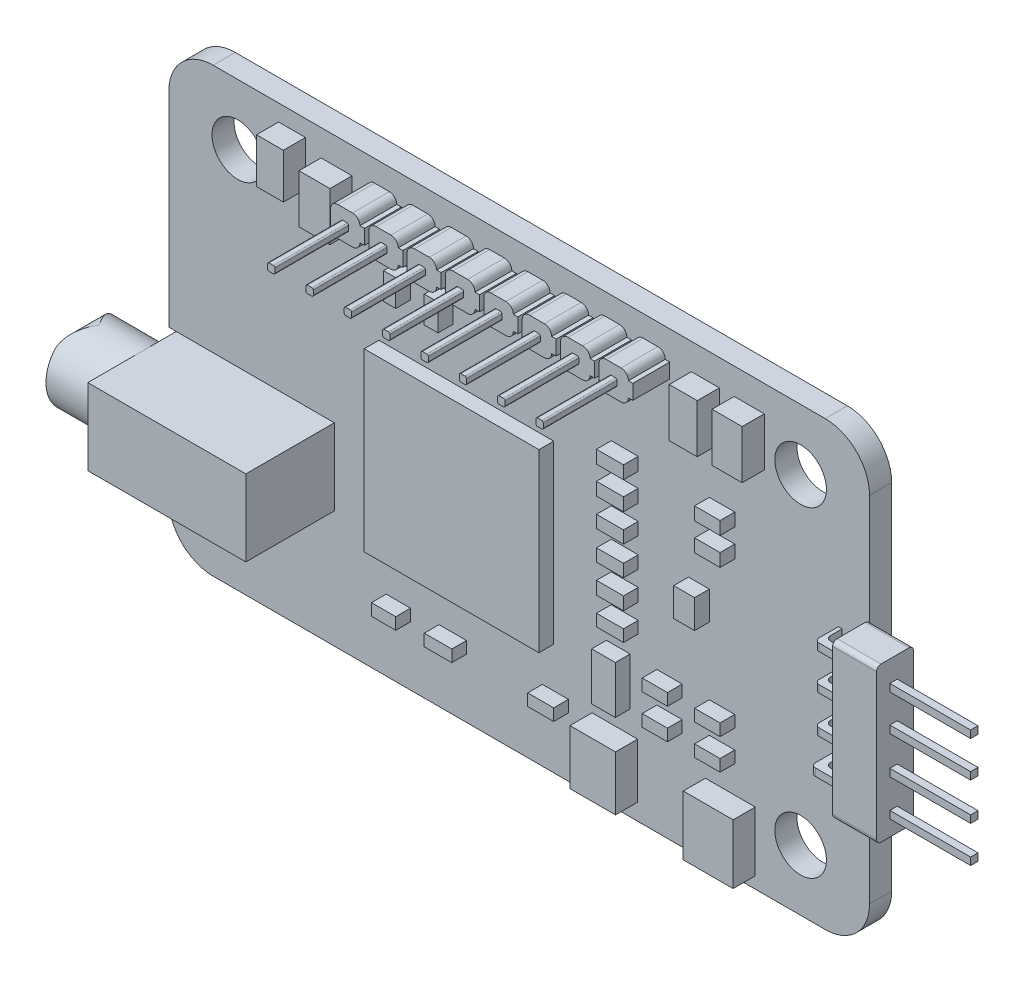
SolidWorks part; units mm, degrees
ref_plane "Alzado" through (0, 0, 0) normal (0, 0, 1) x (1, 0, 0)
ref_plane "Planta" through (0, 0, 0) normal (0, 1, 0) x (1, 0, 0)
ref_plane "Vista lateral" through (0, 0, 0) normal (1, 0, 0) x (0, 0, -1)
sketch "Croquis1" plane through (0, 0, 0) normal (0, 0, 1) x (1, 0, 0)
  line L1 (-20.75, -15) -> (20.75, -15)
  line L2 (-23.75, -12) -> (-23.75, 12)
  line L3 (-20.75, 15) -> (20.75, 15)
  line L4 (23.75, -12) -> (23.75, 12)
  line L5 (-23.75, -15) -> (23.75, 15) construction
  line L6 (-23.75, 15) -> (23.75, -15) construction
  arc A0 (-20.75, -15) -> (-23.75, -12) centre (-20.75, -12) cw
  arc A1 (20.75, -15) -> (23.75, -12) centre (20.75, -12) ccw
  arc A2 (20.75, 15) -> (23.75, 12) centre (20.75, 12) cw
  arc A3 (-23.75, 12) -> (-20.75, 15) centre (-20.75, 12) cw
  point P0 (0, 0)
  dimension "D3" = 3
  dimension "D1" = 47.5
  dimension "D2" = 30
extrude "Saliente-Extruir1" add sketch "Croquis1" along normal blind 1.5 contours L3 A2 L4 A1 L1 A0 L2 A3
sketch "Dibujo_1" plane through (0, 0, 1.5) normal (0, 0, 1) x (1, 0, 0)
  line L0 (72.1693, 147.6706) -> (477.5026, 147.6706) construction
sketch "Croquis3" plane through (0, 0, 1.5) normal (0, 0, 1) x (1, 0, 0)
  circle A0 centre (-19.0796, -10.8807) radius 1.75
  dimension "D1" = 3.5
extrude "Cortar-Extruir1" cut sketch "Croquis3" against normal blind 3
ref_plane "Plano1" through (0, 0, 0) normal (0, -1, 0) x (-1, 0, 0)
ref_plane "Plano2" through (0, 0, 0) normal (-1, 0, 0) x (0, 0, 1)
mirror "Simetría1" about plane through (0, 0, 0) normal (0, -1, 0) of "Cortar-Extruir1"
mirror "Simetría2" about plane through (0, 0, 0) normal (-1, 0, 0) of "Simetría1", "Cortar-Extruir1"
sketch "Croquis4" plane through (0, 0, 1.5) normal (0, 0, 1) x (1, 0, 0)
  line L1 (-9.5072, 4.472) -> (2.338, 4.472)
  line L2 (-9.5072, 4.472) -> (-9.5072, -7.4522)
  line L3 (-9.5072, -7.4522) -> (2.338, -7.4522)
  line L4 (2.338, 4.472) -> (2.338, -7.4522)
extrude "Saliente-Extruir2" add sketch "Croquis4" along normal blind 1
sketch "Croquis5" plane through (0, 0, 1.5) normal (0, 0, 1) x (1, 0, 0)
  line L0 (-8.2982, 13.0504) -> (-7.9934, 13.0504)
  line L1 (-9.7982, 13.5504) -> (-8.7982, 13.5504)
  line L2 (-10.2982, 13.0504) -> (-10.2982, 12.0504)
  line L3 (-9.7982, 11.5504) -> (-8.7982, 11.5504)
  line L4 (-8.2982, 13.0504) -> (-8.2982, 12.0504) construction
  line L5 (-7.9934, 13.0504) -> (-7.9934, 12.0504)
  line L6 (-8.2982, 12.0504) -> (-7.9934, 12.0504)
  arc A0 (-10.2982, 12.0504) -> (-9.7982, 11.5504) centre (-9.7982, 12.0504) ccw
  arc A1 (-8.7982, 11.5504) -> (-8.2982, 12.0504) centre (-8.7982, 12.0504) ccw
  arc A2 (-8.7982, 13.5504) -> (-8.2982, 13.0504) centre (-8.7982, 13.0504) cw
  arc A3 (-9.7982, 13.5504) -> (-10.2982, 13.0504) centre (-9.7982, 13.0504) ccw
  dimension "D1" = 0.5
  dimension "D2" = 2
  dimension "D3" = 2
extrude "Saliente-Extruir3" add sketch "Croquis5" along normal blind 2.5
sketch "Croquis6" plane through (0, 0, 4) normal (0, 0, 1) x (1, 0, 0)
  line L0 (-10.1518, 11.6968) -> (-8.4447, 13.4039) construction
  line L2 (-9.4618, 12.2868) -> (-9.1618, 12.2868)
  line L3 (-9.5618, 12.3868) -> (-9.5618, 12.6868)
  line L4 (-9.4618, 12.7868) -> (-9.1618, 12.7868)
  line L5 (-9.0618, 12.3868) -> (-9.0618, 12.6868)
  line L6 (-9.5618, 12.2868) -> (-9.0618, 12.7868) construction
  arc A2 (-10.2982, 12.0504) -> (-9.7982, 11.5504) centre (-9.7982, 12.0504) ccw construction
  arc A3 (-8.2982, 13.0504) -> (-8.7982, 13.5504) centre (-8.7982, 13.0504) ccw construction
  arc A4 (-9.4618, 12.2868) -> (-9.5618, 12.3868) centre (-9.4618, 12.3868) cw
  arc A5 (-9.1618, 12.2868) -> (-9.0618, 12.3868) centre (-9.1618, 12.3868) ccw
  arc A6 (-9.1618, 12.7868) -> (-9.0618, 12.6868) centre (-9.1618, 12.6868) cw
  arc A7 (-9.5618, 12.6868) -> (-9.4618, 12.7868) centre (-9.4618, 12.6868) cw
  point P8 (-9.2982, 12.5504)
  point P15 (-9.2982, 12.5504)
  point P26 (-9.5618, 12.7868)
  dimension "D3" = 0.1
  dimension "D1" = 0.5
  dimension "D2" = 0.5
extrude "Saliente-Extruir4" add sketch "Croquis6" along normal blind 5
pattern_linear "MatrizL1" count 8 spacing 2.6 along (1, 0, 0) of "Saliente-Extruir3", "Saliente-Extruir4"
sketch "Croquis8" plane through (-23.75, 0, 0) normal (-1, 0, 0) x (0, 0, 1)
  line L0 (1.5, -12) -> (1.5, 12) construction
  line L1 (1.5, -1.8848) -> (0, -1.8848)
  line L2 (1.5, -1.8848) -> (1.5, -7.0554)
  line L3 (1.5, -7.0554) -> (0, -7.0554)
  line L4 (0, -1.8848) -> (0, -7.0554)
  line L5 (0, -12) -> (0, 12) construction
extrude "Saliente-Extruir6" add sketch "Croquis8" along normal blind 3.5
fillet "Redondeo1" radius 1 2 edges at (-27.25, -1.8848, 0.75) (-27.25, -7.0554, 0.75)
ref_plane "Plano4" through (0, 0, 1.5) normal (0, 0, 1) x (1, 0, 0)
sketch "Croquis15" plane through (0, 0, 1.5) normal (0, 0, 1) x (1, 0, 0)
  line L0 (23.75, -12) -> (23.75, 12) construction
  line L1 (23.75, 4.6797) -> (26.7262, 4.6797)
  line L2 (23.75, 4.6797) -> (23.75, 3.24)
  line L3 (23.75, -5.7836) -> (26.7262, -5.7836)
  line L4 (32.2024, 3.24) -> (32.2024, 2.74)
  line L5 (32.2024, 0.7974) -> (32.2024, 0.2974)
  line L6 (32.2024, 2.74) -> (26.7262, 2.74)
  line L7 (23.75, -4.7176) -> (23.75, -5.7836)
  line L8 (32.2024, 0.7974) -> (26.7262, 0.7974)
  line L9 (26.7262, 2.74) -> (26.7262, 0.7974)
  line L10 (32.2024, 0.2974) -> (26.7262, 0.2974)
  line L11 (23.75, 3.24) -> (21.6534, 3.24)
  line L12 (32.2024, -1.7425) -> (26.7262, -1.7425)
  line L13 (26.7262, 0.2974) -> (26.7262, -1.7425)
  line L14 (32.2024, -2.2425) -> (26.7262, -2.2425)
  line L15 (23.75, -2.2425) -> (23.75, -4.2176)
  line L16 (32.2024, -4.2176) -> (26.7262, -4.2176)
  line L17 (26.7262, -2.2425) -> (26.7262, -4.2176)
  line L18 (23.75, 0.2974) -> (23.75, -1.7425)
  line L19 (23.75, 2.74) -> (23.75, 0.7974)
  line L20 (32.2024, -4.7176) -> (26.7262, -4.7176)
  line L21 (26.7262, -5.7836) -> (26.7262, -4.7176)
  line L24 (32.2024, 3.24) -> (26.7262, 3.24)
  line L25 (26.7262, 4.6797) -> (26.7262, 3.24)
  line L26 (32.2024, -1.7425) -> (32.2024, -2.2425)
  line L27 (32.2024, -4.2176) -> (32.2024, -4.7176)
  line L29 (23.75, 2.74) -> (21.6534, 2.74)
  line L30 (21.6534, 3.24) -> (21.6534, 2.74)
  line L31 (23.75, 0.7974) -> (21.6534, 0.7974)
  line L33 (23.75, 0.2974) -> (21.6534, 0.2974)
  line L34 (21.6534, 0.7974) -> (21.6534, 0.2974)
  line L35 (23.75, -1.7425) -> (21.6534, -1.7425)
  line L37 (23.75, -2.2425) -> (21.6534, -2.2425)
  line L38 (21.6534, -1.7425) -> (21.6534, -2.2425)
  line L39 (23.75, -4.2176) -> (21.4013, -4.2176)
  line L41 (23.75, -4.7176) -> (21.4013, -4.7176)
  line L42 (21.4013, -4.2176) -> (21.4013, -4.7176)
  dimension "D1" = 0.5
  dimension "D2" = 0.5
  dimension "D3" = 0.5
  dimension "D4" = 0.5
extrude "Saliente-Extruir9" add sketch "Croquis15" along normal blind 2.5 separate body
sketch "Croquis16" plane through (0, -4.7176, 0) normal (0, -1, 0) x (1, 0, 0)
  line L0 (26.7262, 4) -> (26.7262, 1.5) construction
  line L1 (32.2024, 4) -> (26.7262, 4)
  line L2 (32.2024, 4) -> (32.2024, 3.0973)
  line L3 (32.2024, 3.0973) -> (26.7262, 3.0973)
  line L4 (26.7262, 4) -> (26.7262, 3.0973)
  line L6 (32.2024, 1.5) -> (26.7262, 1.5)
  line L7 (32.2024, 1.5) -> (32.2024, 2.5973)
  line L8 (32.2024, 2.5973) -> (26.7262, 2.5973)
  line L9 (26.7262, 1.5) -> (26.7262, 2.5973)
  dimension "D1" = 0.5
extrude "Cortar-Extruir5" cut sketch "Croquis16" against normal through all
sketch "Croquis17" plane through (0, -4.7176, 0) normal (0, -1, 0) x (1, 0, 0)
  line L0 (21.4013, 4) -> (21.4013, 1.5) construction
  line L1 (23.75, 4) -> (21.4013, 4)
  line L2 (23.75, 4) -> (23.75, 3.1227)
  line L3 (23.75, 3.1227) -> (21.4013, 3.1227)
  line L4 (21.4013, 4) -> (21.4013, 3.1227)
  line L5 (23.75, 4) -> (23.75, 1.5) construction
  line L6 (21.9013, 1.5) -> (23.75, 1.5)
  line L8 (22.2013, 2.6227) -> (23.75, 2.6227)
  line L9 (23.75, 1.5) -> (23.75, 2.6227)
  line L15 (21.9013, 1.5) -> (21.9013, 2.3227)
  arc A0 (22.2013, 2.6227) -> (21.9013, 2.3227) centre (22.2013, 2.3227) ccw
  dimension "D3" = 0.3
  dimension "D1" = 0.5
  dimension "D2" = 0.5
extrude "Cortar-Extruir6" cut sketch "Croquis17" against normal through all
fillet "Redondeo3" radius 0.3 4 edges at (21.6534, -1.9925, 3.1227) (21.6534, 0.5474, 3.1227) (21.6534, 2.99, 3.1227) (21.4013, -4.4676, 3.1227)
fillet "Redondeo4" radius 0.3 4 edges at (25.2381, 4.6797, 1.5) (25.2381, -5.7836, 1.5) (25.2381, 4.6797, 4) (25.2381, -5.7836, 4)
sketch "Croquis18" plane through (0, 0, 1.5) normal (0, 0, 1) x (1, 0, 0)
  line L1 (14.5768, 13.215) -> (16.6151, 13.215)
  line L2 (14.5768, 13.215) -> (14.5768, 9.9176)
  line L3 (14.5768, 9.9176) -> (16.6151, 9.9176)
  line L4 (16.6151, 13.215) -> (16.6151, 9.9176)
  line L5 (11.673, 13.215) -> (13.5693, 13.215)
  line L6 (11.673, 13.215) -> (11.673, 9.9176)
  line L7 (11.673, 9.9176) -> (13.5693, 9.9176)
  line L8 (13.5693, 13.215) -> (13.5693, 9.9176)
  line L9 (-13.4312, 13.215) -> (-11.3327, 13.215)
  line L10 (-13.4312, 13.215) -> (-13.4312, 9.9176)
  line L11 (-13.4312, 9.9176) -> (-11.3327, 9.9176)
  line L12 (-11.3327, 13.215) -> (-11.3327, 9.9176)
  line L13 (-14.4891, 10.8428) -> (-16.3087, 10.8428)
  line L14 (-14.4891, 10.8428) -> (-14.4891, 13.8863)
  line L15 (-14.4891, 13.8863) -> (-16.3087, 13.8863)
  line L16 (-16.3087, 10.8428) -> (-16.3087, 13.8863)
  line L17 (4.9383, -10.1782) -> (8.03, -10.1782)
  line L18 (4.9383, -10.1782) -> (4.9383, -13.879)
  line L19 (4.9383, -13.879) -> (8.03, -13.879)
  line L20 (8.03, -10.1782) -> (8.03, -13.879)
  line L21 (12.6211, -10.1782) -> (16.0032, -10.1782)
  line L22 (12.6211, -10.1782) -> (12.6211, -14.2179)
  line L23 (12.6211, -14.2179) -> (16.0032, -14.2179)
  line L24 (16.0032, -10.1782) -> (16.0032, -14.2179)
extrude "Saliente-Extruir10" add sketch "Croquis18" along normal blind 1.5
sketch "Croquis19" plane through (0, 0, 1.5) normal (0, 0, 1) x (1, 0, 0)
  line L1 (6.2413, 6.4483) -> (8.071, 6.4483)
  line L2 (6.2413, 6.4483) -> (6.2413, 5.569)
  line L3 (6.2413, 5.569) -> (8.071, 5.569)
  line L4 (8.071, 6.4483) -> (8.071, 5.569)
  line L5 (6.2413, 4.5685) -> (8.071, 4.5685)
  line L6 (6.2413, 4.5685) -> (6.2413, 3.6937)
  line L7 (6.2413, 3.6937) -> (8.071, 3.6937)
  line L8 (8.071, 4.5685) -> (8.071, 3.6937)
  line L9 (6.2413, 2.6282) -> (8.071, 2.6282)
  line L10 (6.2413, 2.6282) -> (6.2413, 1.7851)
  line L11 (6.2413, 1.7851) -> (8.071, 1.7851)
  line L12 (8.071, 2.6282) -> (8.071, 1.7851)
  line L13 (6.2413, 0.6637) -> (8.071, 0.6637)
  line L14 (6.2413, 0.6637) -> (6.2413, -0.1839)
  line L15 (6.2413, -0.1839) -> (8.071, -0.1839)
  line L16 (8.071, 0.6637) -> (8.071, -0.1839)
  line L17 (6.2413, -1.2493) -> (8.071, -1.2493)
  line L18 (6.2413, -1.2493) -> (6.2413, -2.1212)
  line L19 (6.2413, -2.1212) -> (8.071, -2.1212)
  line L20 (8.071, -1.2493) -> (8.071, -2.1212)
  line L21 (6.2413, -3.182) -> (8.071, -3.182)
  line L22 (6.2413, -3.182) -> (6.2413, -3.9849)
  line L23 (6.2413, -3.9849) -> (8.071, -3.9849)
  line L24 (8.071, -3.182) -> (8.071, -3.9849)
  line L25 (9.3357, -5.4351) -> (11.0496, -5.4351)
  line L26 (9.3357, -5.4351) -> (9.3357, -6.2406)
  line L27 (9.3357, -6.2406) -> (11.0496, -6.2406)
  line L28 (11.0496, -5.4351) -> (11.0496, -6.2406)
  line L29 (9.3357, -7.5241) -> (11.0496, -7.5241)
  line L30 (9.3357, -7.5241) -> (9.3357, -8.327)
  line L31 (9.3357, -8.327) -> (11.0496, -8.327)
  line L32 (11.0496, -7.5241) -> (11.0496, -8.327)
  line L33 (12.8907, -7.5241) -> (14.6147, -7.5241)
  line L34 (12.8907, -7.5241) -> (12.8907, -8.327)
  line L35 (12.8907, -8.327) -> (14.6147, -8.327)
  line L36 (14.6147, -7.5241) -> (14.6147, -8.327)
  line L37 (12.8907, -5.4351) -> (14.6147, -5.4351)
  line L38 (12.8907, -5.4351) -> (12.8907, -6.2406)
  line L39 (12.8907, -6.2406) -> (14.6147, -6.2406)
  line L40 (14.6147, -5.4351) -> (14.6147, -6.2406)
  line L41 (12.8907, 4.5685) -> (14.6147, 4.5685)
  line L42 (12.8907, 4.5685) -> (12.8907, 3.6937)
  line L43 (12.8907, 3.6937) -> (14.6147, 3.6937)
  line L44 (14.6147, 4.5685) -> (14.6147, 3.6937)
  line L45 (12.8907, 6.4483) -> (14.6147, 6.4483)
  line L46 (12.8907, 6.4483) -> (12.8907, 5.569)
  line L47 (12.8907, 5.569) -> (14.6147, 5.569)
  line L48 (14.6147, 6.4483) -> (14.6147, 5.569)
  line L49 (-9.0191, -10.1891) -> (-7.3707, -10.1891)
  line L50 (-9.0191, -10.1891) -> (-9.0191, -10.9907)
  line L51 (-9.0191, -10.9907) -> (-7.3707, -10.9907)
  line L52 (-7.3707, -10.1891) -> (-7.3707, -10.9907)
  line L53 (-5.4372, -10.1891) -> (-3.5716, -10.1891)
  line L54 (-5.4372, -10.1891) -> (-5.4372, -10.9907)
  line L55 (-5.4372, -10.9907) -> (-3.5716, -10.9907)
  line L56 (-3.5716, -10.1891) -> (-3.5716, -10.9907)
  line L57 (1.5761, -10.1891) -> (3.3382, -10.1891)
  line L58 (1.5761, -10.1891) -> (1.5761, -10.9907)
  line L59 (1.5761, -10.9907) -> (3.3382, -10.9907)
  line L60 (3.3382, -10.1891) -> (3.3382, -10.9907)
  line L61 (11.4778, 1.0598) -> (12.8907, 1.0598)
  line L62 (11.4778, 1.0598) -> (11.4778, -0.8762)
  line L63 (11.4778, -0.8762) -> (12.8907, -0.8762)
  line L64 (12.8907, 1.0598) -> (12.8907, -0.8762)
  line L65 (5.9125, -5.4351) -> (7.5178, -5.4351)
  line L66 (5.9125, -5.4351) -> (5.9125, -8.6662)
  line L67 (5.9125, -8.6662) -> (7.5178, -8.6662)
  line L68 (7.5178, -5.4351) -> (7.5178, -8.6662)
  line L69 (-5.4372, 9.7155) -> (-4.5044, 9.7155)
  line L70 (-5.4372, 9.7155) -> (-5.4372, 7.9048)
  line L71 (-5.4372, 7.9048) -> (-4.5044, 7.9048)
  line L72 (-4.5044, 9.7155) -> (-4.5044, 7.9048)
  line L73 (-8.1949, 9.7155) -> (-7.3707, 9.7155)
  line L74 (-8.1949, 9.7155) -> (-8.1949, 7.9048)
  line L75 (-8.1949, 7.9048) -> (-7.3707, 7.9048)
  line L76 (-7.3707, 9.7155) -> (-7.3707, 7.9048)
extrude "Saliente-Extruir11" add sketch "Croquis19" along normal blind 1
sketch "Croquis21" plane through (0, 0, 1.5) normal (0, 0, 1) x (1, 0, 0)
  line L0 (-26.25, -1.8848) -> (-23.75, -1.8848) construction
  line L1 (-27.25, -6.0554) -> (-27.25, -2.8848) construction
  line L2 (-26.25, -7.0554) -> (-23.75, -7.0554) construction
  line L3 (-26.25, -7.0554) -> (-23.75, -7.0554)
  line L4 (-27.25, -6.0554) -> (-27.25, -2.8848)
  line L5 (-26.25, -1.8848) -> (-23.75, -1.8848)
  line L7 (-23.75, -1.8848) -> (-12.5306, -1.8848)
  line L9 (-23.75, -7.0554) -> (-12.5306, -7.0554)
  line L10 (-12.5306, -1.8848) -> (-12.5306, -7.0554)
  arc A0 (-27.25, -6.0554) -> (-26.25, -7.0554) centre (-26.25, -6.0554) ccw construction
  arc A1 (-26.25, -1.8848) -> (-27.25, -2.8848) centre (-26.25, -2.8848) ccw construction
  arc A2 (-27.25, -6.0554) -> (-26.25, -7.0554) centre (-26.25, -6.0554) ccw
  arc A3 (-26.25, -1.8848) -> (-27.25, -2.8848) centre (-26.25, -2.8848) ccw
extrude "Saliente-Extruir12" add sketch "Croquis21" along normal blind 6
ref_plane "Plano5" through (-27.25, 0, 0) normal (-1, 0, 0) x (0, 0, 1)
sketch "Croquis23" plane through (-27.25, 0, 0) normal (-1, 0, 0) x (0, 0, 1)
  line L0 (7.5, -4.4701) -> (0, -4.4701) construction
  line L1 (7.5, -2.8848) -> (7.5, -6.0554) construction
  line L2 (0, -2.8848) -> (0, -6.0554) construction
  line L3 (0, -1.8848) -> (7.5, -1.8848) construction
  line L4 (0, -1.8848) -> (7.5, -1.8848)
  line L5 (7.5, -7.0554) -> (0, -7.0554) construction
  line L6 (7.5, -7.0554) -> (0, -7.0554)
  line L7 (7.5, -1.8848) -> (7.5, -7.0554)
  line L8 (0, -1.8848) -> (0, -7.0554)
  circle A0 centre (3.75, -4.4701) radius 2.5853
extrude "Cortar-Extruir7" cut sketch "Croquis23" against normal blind 4 contours L0 L7 L4 A0 | L7 L0 A0 L6 | L0 A0 L4 L8 | A0 L0 L8 L6
sketch "Croquis24" plane through (-27.25, 0, 0) normal (-1, 0, 0) x (0, 0, 1)
  circle A0 centre (3.75, -4.4701) radius 1.25
  dimension "D1" = 2.5
extrude "Cortar-Extruir8" cut sketch "Croquis24" against normal blind 10
